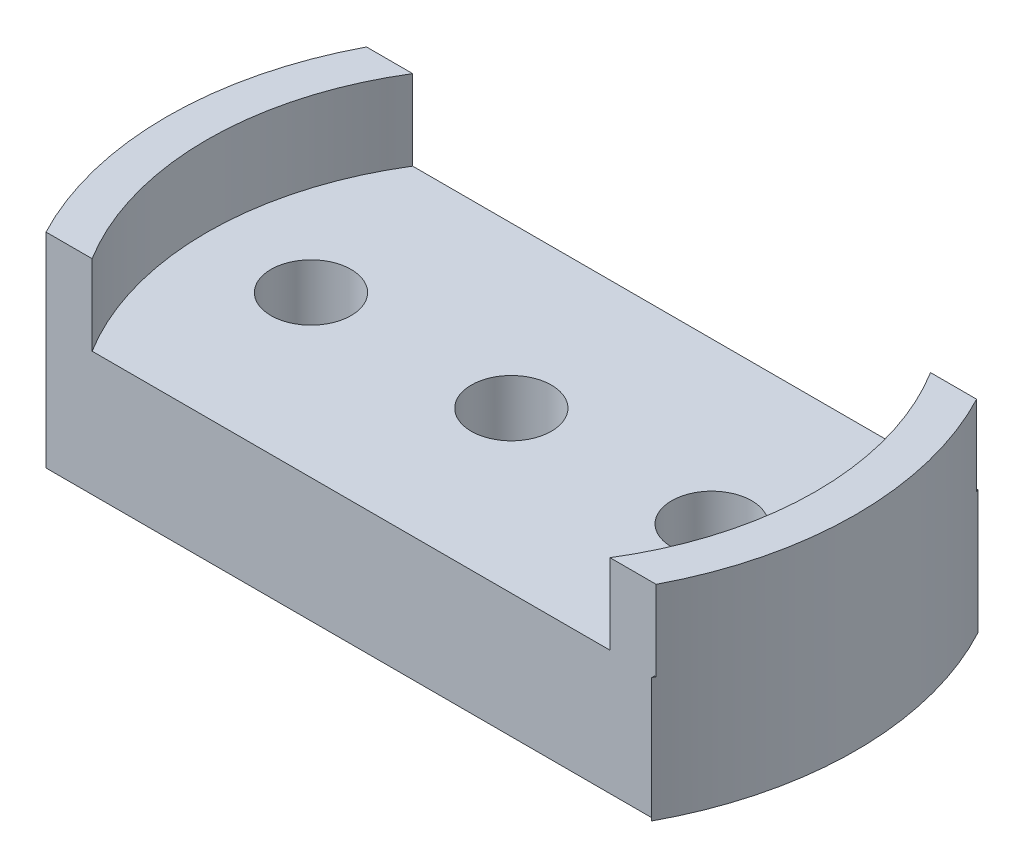
SolidWorks part; units mm, degrees
ref_plane "Front Plane" through (0, 0, 0) normal (0, 0, 1) x (1, 0, 0)
ref_plane "Top Plane" through (0, 0, 0) normal (0, 1, 0) x (1, 0, 0)
ref_plane "Right Plane" through (0, 0, 0) normal (1, 0, 0) x (0, 0, -1)
sketch "Sketch3" plane through (0, 0, 0) normal (0, 1, 0) x (1, 0, 0)
  circle A0 centre (0, 0) radius 43
  dimension "D1" = 86
extrude "Boss-Extrude2" add sketch "Sketch3" along normal blind 15.5
sketch "Sketch4" plane through (0, 15.5, 0) normal (0, 1, 0) x (1, 0, 0)
  line L1 (-38.0657, 20) -> (-32.311, 20)
  line L3 (-38.0657, -20) -> (-32.311, -20)
  line L8 (32.311, 20) -> (38.0657, 20)
  line L9 (32.311, -20) -> (38.0657, -20)
  arc A0 (-38.0657, 20) -> (-38.0657, -20) centre (0, 0) ccw
  arc A1 (-32.311, 20) -> (-32.311, -20) centre (0, 0) ccw
  arc A2 (38.0657, -20) -> (38.0657, 20) centre (0, 0) ccw
  arc A3 (32.311, -20) -> (32.311, 20) centre (0, 0) ccw
  dimension "D1" = 76
extrude "Boss-Extrude5" add sketch "Sketch4" along normal blind 10
sketch "Sketch9" plane through (0, 15.5, 0) normal (0, 1, 0) x (1, 0, 0)
  line L0 (0, 0) -> (18.7091, 0) construction
  line L1 (-38.0657, -20) -> (37.8745, -20)
  line L2 (-38.0657, -20) -> (-38.0657, -44.0348)
  line L3 (-38.0657, -44.0348) -> (37.8745, -44.0348)
  line L4 (37.8745, -20) -> (37.8745, -44.0348)
  line L5 (-38.0657, 44.0348) -> (37.8745, 44.0348)
  line L6 (37.8745, 20) -> (37.8745, 44.0348)
  line L7 (-38.0657, 20) -> (37.8745, 20)
  line L8 (-38.0657, 20) -> (-38.0657, 44.0348)
extrude "Cut-Extrude8" cut sketch "Sketch9" against normal blind 20
sketch "Sketch10" plane through (0, 0, 0) normal (0, -1, 0) x (1, 0, 0)
  circle A0 centre (0, 0) radius 5
  dimension "D1" = 10
extrude "Cut-Extrude9" cut sketch "Sketch10" against normal blind 20
sketch "Sketch11" plane through (0, 0, 0) normal (0, -1, 0) x (1, 0, 0)
  line L0 (0, 0) -> (25, 0) construction
  line L1 (0, 0) -> (0, -18.6002) construction
  circle A0 centre (25, 0) radius 5
  circle A1 centre (-25, 0) radius 5
  dimension "D2" = 10
  dimension "D1" = 25
extrude "Cut-Extrude10" cut sketch "Sketch11" against normal blind 20
